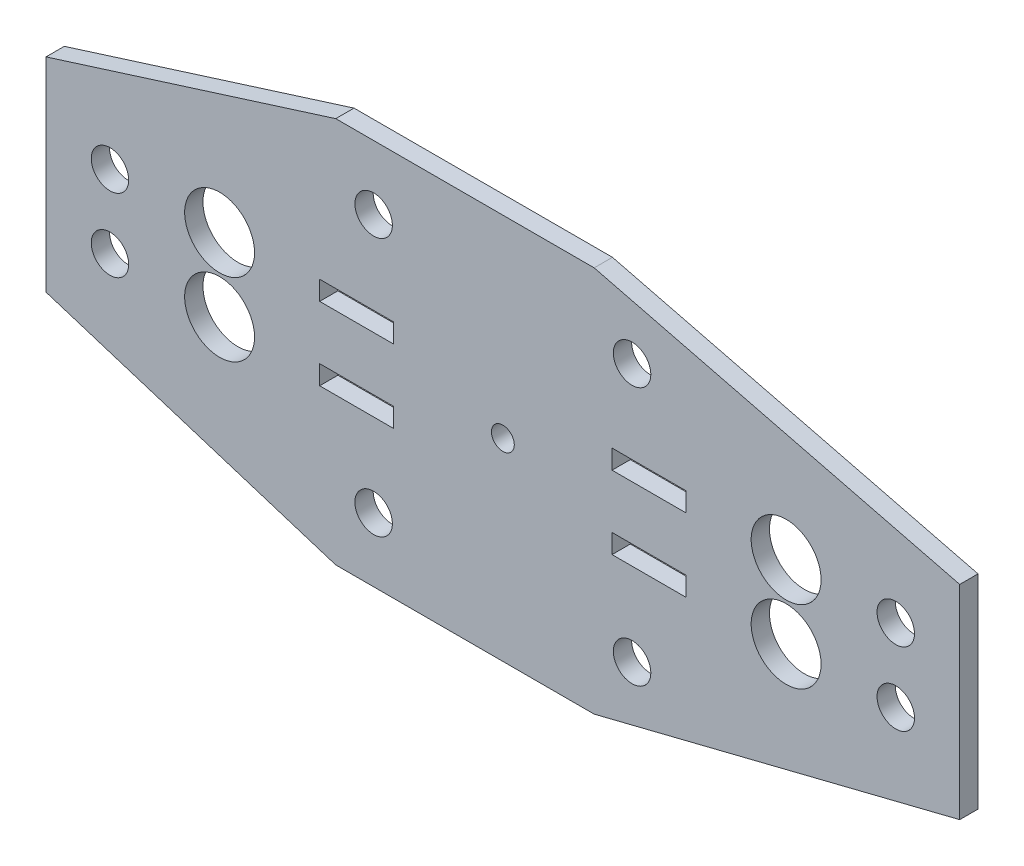
SolidWorks part; units mm, degrees
ref_plane "前视基准面" through (0, 0, 0) normal (0, 0, 1) x (1, 0, 0)
ref_plane "上视基准面" through (0, 0, 0) normal (0, 1, 0) x (1, 0, 0)
ref_plane "右视基准面" through (0, 0, 0) normal (1, 0, 0) x (0, 0, -1)
sketch "草图1" plane through (0, 0, 0) normal (0, 0, 1) x (1, 0, 0)
  line L0 (0, 0) -> (0, -8) construction
  line L1 (0, 0) -> (15, 0)
  line L2 (0, 0) -> (62, 0) construction
  line L3 (19.05, -1.05) -> (10.95, -1.05)
  line L4 (19.05, -1.05) -> (19.05, 1.05)
  line L5 (19.05, 1.05) -> (10.95, 1.05)
  line L6 (10.95, -1.05) -> (10.95, 1.05)
  line L7 (19.05, -1.05) -> (10.95, 1.05) construction
  line L8 (19.05, 1.05) -> (10.95, -1.05) construction
  line L9 (31, 0) -> (31, -4) construction
  line L10 (42.95, -1.05) -> (51.05, -1.05)
  line L11 (42.95, -1.05) -> (42.95, 1.05)
  line L12 (51.05, -1.05) -> (51.05, 1.05)
  line L13 (42.95, 1.05) -> (51.05, 1.05)
  line L14 (0, -4) -> (2.5207, -4) construction
  line L15 (51.05, -6.95) -> (51.05, -9.05)
  line L16 (42.95, -6.95) -> (42.95, -9.05)
  line L17 (42.95, -9.05) -> (51.05, -9.05)
  line L18 (42.95, -6.95) -> (51.05, -6.95)
  line L19 (19.05, -6.95) -> (19.05, -9.05)
  line L20 (10.95, -6.95) -> (10.95, -9.05)
  line L21 (19.05, -6.95) -> (10.95, -6.95)
  line L22 (19.05, -9.05) -> (10.95, -9.05)
  line L23 (31, -4) -> (31, 30.555) construction
  line L24 (81, -15.1497) -> (-19, -15.1497) construction
  line L25 (81, -15.1497) -> (81, 7.1497)
  line L26 (81, 7.1497) -> (-19, 7.1497) construction
  line L27 (-19, -15.1497) -> (-19, 7.1497)
  line L28 (81, -15.1497) -> (-19, 7.1497) construction
  line L29 (81, 7.1497) -> (-19, -15.1497) construction
  line L30 (31, -4) -> (54.6995, 19.6995) construction
  line L31 (-19, 7.1497) -> (12.7087, 17.1497)
  line L32 (12.7087, 17.1497) -> (40.993, 17.1497)
  line L33 (40.993, 17.1497) -> (81, 7.1497)
  line L34 (31, -4) -> (84.8449, -4) construction
  line L35 (12.7087, -25.1497) -> (40.993, -25.1497)
  line L36 (40.993, -25.1497) -> (81, -15.1497)
  line L37 (-19, -15.1497) -> (12.7087, -25.1497)
  line L38 (62, 0) -> (74, 0) construction
  circle A0 centre (0, 0) radius 3.825
  circle A1 centre (62, 0) radius 3.825
  circle A2 centre (62, -8) radius 3.825
  circle A3 centre (0, -8) radius 3.825
  circle A5 centre (31, -4) radius 20 construction
  circle A6 centre (45.1421, 10.1421) radius 2.05
  circle A7 centre (45.1421, -18.1421) radius 2.05
  circle A8 centre (16.8579, -18.1421) radius 2.05
  circle A9 centre (16.8579, 10.1421) radius 2.05
  circle A11 centre (74, 0) radius 2.05
  circle A12 centre (74, -8) radius 2.05
  circle A13 centre (-12, -8) radius 2.05
  circle A14 centre (-12, 0) radius 2.05
  circle A15 centre (31, -4) radius 1.25
  circle A16 centre (31, -4) radius 5 construction
  dimension "D2" = 7.65
  dimension "D8" = 4
  dimension "D10" = 12
  dimension "D12" = 2.5
  dimension "D1" = 8
  dimension "D3" = 15
  dimension "D4" = 8.1
  dimension "D5" = 2.1
  dimension "D6" = 62
  dimension "D7" = 45
  dimension "D9" = 10
  dimension "D11" = 100
extrude "凸台-拉伸1" add sketch "草图1" along normal blind 2
